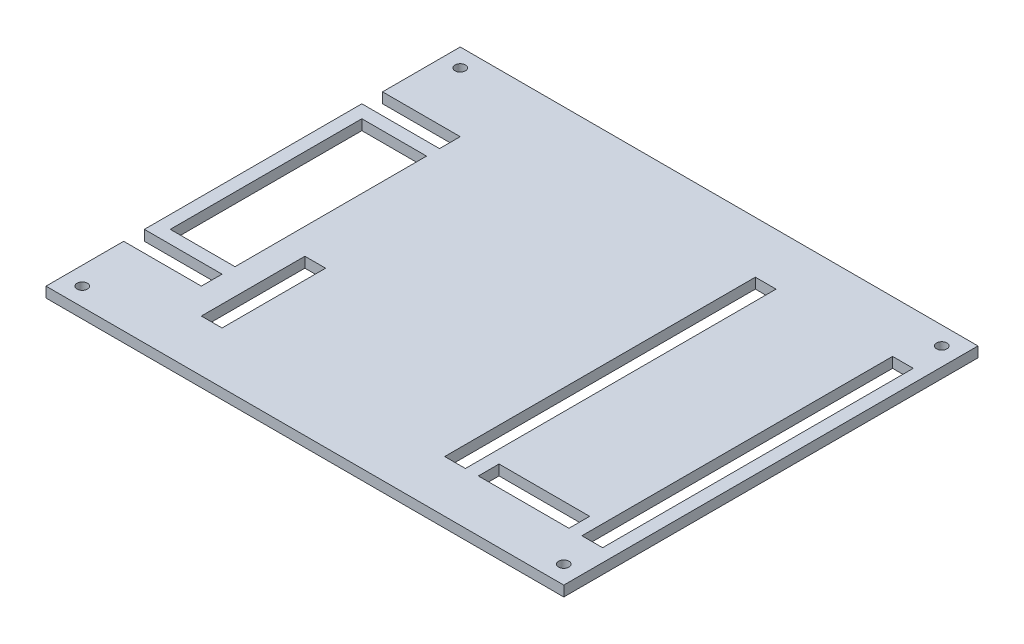
SolidWorks part; units mm, degrees
ref_plane "Front Plane" through (0, 0, 0) normal (0, 0, 1) x (1, 0, 0)
ref_plane "Top Plane" through (0, 0, 0) normal (0, 1, 0) x (1, 0, 0)
ref_plane "Right Plane" through (0, 0, 0) normal (1, 0, 0) x (0, 0, -1)
sketch "Sketch3" plane through (0, 0, 0) normal (0, 1, 0) x (1, 0, 0)
  line L1 (100, 80) -> (-100, 80)
  line L2 (100, 80) -> (100, -80)
  line L3 (100, -80) -> (-100, -80)
  line L4 (-100, 80) -> (-100, -80)
  line L5 (100, 80) -> (-100, -80) construction
  line L6 (100, -80) -> (-100, 80) construction
  point P0 (0, 0)
  dimension "D1" = 200
  dimension "D2" = 160
extrude "Boss-Extrude1" add sketch "Sketch3" along normal blind 4
sketch "Sketch4" plane through (0, 4, 0) normal (0, 1, 0) x (1, 0, 0)
  line L0 (-100, 80) -> (-100, -80) construction
  line L1 (100, 80) -> (-100, 80) construction
  line L2 (100, -80) -> (100, 80) construction
  line L3 (-100, -80) -> (100, -80) construction
  circle A0 centre (-93, 73) radius 2
  circle A1 centre (93, 73) radius 2
  circle A2 centre (-93, -73) radius 2
  circle A3 centre (93, -73) radius 2
  dimension "D1" = 4
  dimension "D2" = 7
  dimension "D3" = 7
  dimension "D4" = 4
  dimension "D5" = 7
  dimension "D6" = 7
  dimension "D7" = 4
  dimension "D8" = 7
  dimension "D9" = 7
  dimension "D10" = 4
  dimension "D11" = 7
  dimension "D12" = 7
extrude "Cut-Extrude1" cut sketch "Sketch4" against normal through all contours A3 | A2 | A1 | A0
sketch "Sketch5" plane through (0, 4, 0) normal (0, 1, 0) x (1, 0, 0)
  line L0 (-100, 42) -> (-70, 42)
  line L1 (-100, 80) -> (-100, -80) construction
  line L2 (-70, 50) -> (-100, 50)
  line L3 (-70, 42) -> (-70, 50)
  line L4 (-100, -42) -> (-70, -42)
  line L5 (-70, -42) -> (-70, -50)
  line L6 (-70, -50) -> (-100, -50)
  line L7 (100, 80) -> (-100, 80) construction
  line L8 (-100, -80) -> (100, -80) construction
  dimension "D1" = 38
  dimension "D2" = 8
  dimension "D3" = 30
  dimension "D4" = 30
  dimension "D5" = 8
  dimension "D6" = 30
  dimension "D7" = 30
sketch "Sketch7" plane through (0, 4, 0) normal (0, 1, 0) x (1, 0, 0)
  line L0 (-100, 42) -> (-70, 42) construction
  line L1 (-70, -37) -> (-95, -37)
  line L2 (-70, -37) -> (-70, 37)
  line L3 (-70, 37) -> (-95, 37)
  line L4 (-95, -37) -> (-95, 37)
  line L5 (-70, -37) -> (-95, 37) construction
  line L6 (-70, 37) -> (-95, -37) construction
  line L7 (-100, -42) -> (-70, -42) construction
  line L8 (-100, 80) -> (-100, -80) construction
  point P0 (-82.5, 0)
  dimension "D1" = 5
  dimension "D2" = 5
  dimension "D3" = 5
  dimension "D4" = 25
extrude "Cut-Extrude3" cut sketch "Sketch5" against normal through all and the other way through all contours L0 L3 L2
extrude "Cut-Extrude4" cut sketch "Sketch7" against normal through all contours L3 L4 L1 L2
sketch "Sketch11" plane through (0, 4, 0) normal (0, 1, 0) x (1, 0, 0)
  line L0 (100, 0) -> (-88.7689, 0) construction
  line L1 (100, -80) -> (100, 80) construction
  line L2 (-100, -42) -> (-70, -42)
  line L3 (-100, 42) -> (-100, -80) construction
  line L4 (-70, -42) -> (-70, -50)
  line L5 (-70, -50) -> (-100, -50)
  line L6 (-100, -80) -> (100, -80) construction
  line L7 (-70, -37) -> (-95, -37) construction
  dimension "D1" = 30
  dimension "D2" = 5
  dimension "D3" = 8
  dimension "D4" = 30
extrude "Cut-Extrude6" cut sketch "Sketch11" against normal blind 4 and the other way through all flip side to cut
sketch "Sketch12" plane through (0, 4, 0) normal (0, 1, 0) x (1, 0, 0)
  line L0 (100, -80) -> (100, 80) construction
  line L1 (95, 60) -> (87, 60)
  line L2 (95, 60) -> (95, -60)
  line L3 (95, -60) -> (87, -60)
  line L4 (87, 60) -> (87, -60)
  line L5 (100, 80) -> (-100, 80) construction
  line L6 (-100, -80) -> (100, -80) construction
  line L8 (34, 60) -> (42, 60)
  line L9 (34, 60) -> (34, -60)
  line L10 (34, -60) -> (42, -60)
  line L11 (42, 60) -> (42, -60)
  dimension "D1" = 5
  dimension "D2" = 8
  dimension "D3" = 20
  dimension "D4" = 20
  dimension "D5" = 45
  dimension "D6" = 8
  dimension "D7" = 20
  dimension "D8" = 20
extrude "Cut-Extrude8" cut sketch "Sketch12" against normal through all contours L4 L3 L2 L1
sketch "Sketch14" plane through (0, 4, 0) normal (0, 1, 0) x (1, 0, 0)
  line L0 (87, 60) -> (87, -60) construction
  line L1 (34, 60) -> (42, 60)
  line L2 (34, 60) -> (34, -60)
  line L3 (34, -60) -> (42, -60)
  line L4 (42, 60) -> (42, -60)
  line L5 (100, 80) -> (-100, 80) construction
  line L6 (-100, -80) -> (100, -80) construction
  dimension "D1" = 45
  dimension "D2" = 8
  dimension "D3" = 20
  dimension "D4" = 20
extrude "Cut-Extrude9" cut sketch "Sketch14" against normal through all
sketch "Sketch15" plane through (0, 4, 0) normal (0, 1, 0) x (1, 0, 0)
  line L0 (-100, -50) -> (-100, -80) construction
  line L1 (-52, -20) -> (-60, -20)
  line L2 (-52, -20) -> (-52, -60)
  line L3 (-52, -60) -> (-60, -60)
  line L4 (-60, -20) -> (-60, -60)
  line L5 (-100, -80) -> (100, -80) construction
  dimension "D1" = 8
  dimension "D2" = 40
  dimension "D3" = 20
  dimension "D4" = 40
extrude "Cut-Extrude10" cut sketch "Sketch15" against normal through all
sketch "Sketch16" plane through (0, 4, 0) normal (0, 1, 0) x (1, 0, 0)
  line L0 (-100, -80) -> (100, -80) construction
  line L1 (82, -52) -> (47, -52)
  line L2 (82, -52) -> (82, -60)
  line L3 (82, -60) -> (47, -60)
  line L4 (47, -52) -> (47, -60)
  line L5 (87, 60) -> (87, -60) construction
  line L6 (42, -60) -> (42, 60) construction
  dimension "D1" = 20
  dimension "D2" = 8
  dimension "D3" = 5
  dimension "D4" = 5
extrude "Cut-Extrude11" cut sketch "Sketch16" against normal through all
